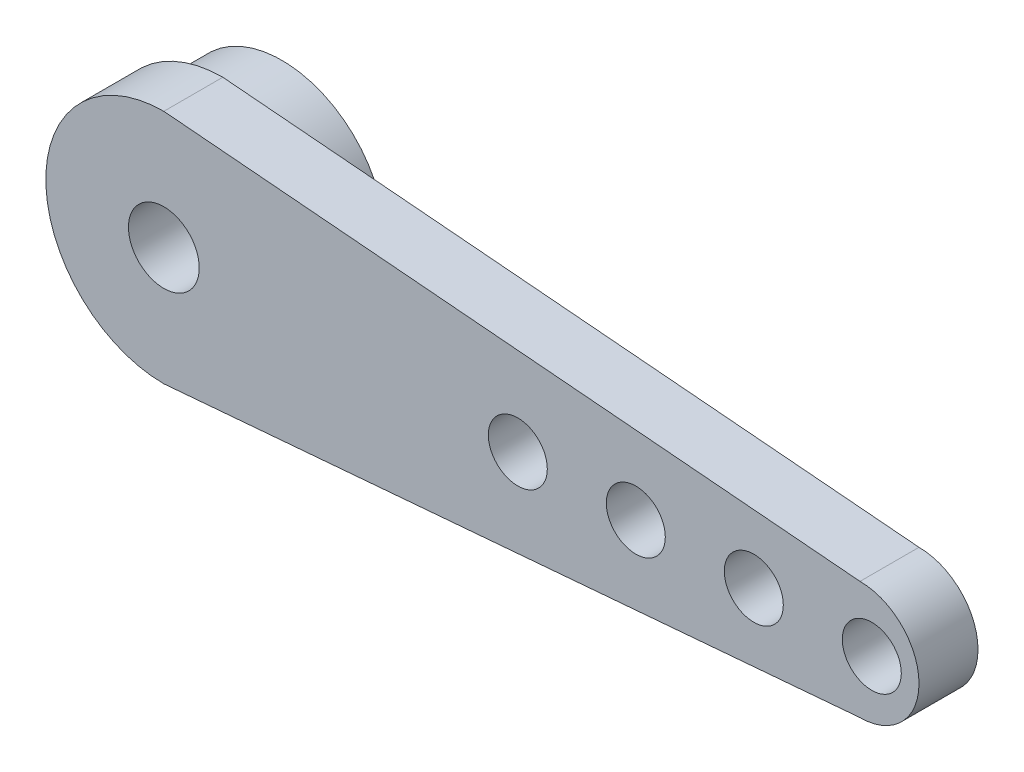
SolidWorks part; units mm, degrees
material "6061 Alloy"
ref_plane "Front Plane" through (0, 0, 0) normal (0, 0, 1) x (1, 0, 0)
ref_plane "Top Plane" through (0, 0, 0) normal (0, 1, 0) x (1, 0, 0)
ref_plane "Right Plane" through (0, 0, 0) normal (1, 0, 0) x (0, 0, -1)
sketch "Sketch1" plane through (0, 0, 0) normal (0, 0, 1) x (1, 0, 0)
  line L0 (0, 0) -> (27.5918, 0) construction
  line L1 (0, 5) -> (29.5, 2.5)
  line L2 (0, -5) -> (29.5, -2.5)
  line L3 (32, 0) -> (50.4925, 0) construction
  arc A0 (0.8414, 4.9287) -> (0.8414, -4.9287) centre (0, 0) ccw
  arc A1 (29.5, -2.5) -> (29.5, 2.5) centre (29.5, 0) ccw
  circle A2 centre (0, 0) radius 1.5
  circle A4 centre (15, 0) radius 1.25
  circle A5 centre (20, 0) radius 1.25
  circle A6 centre (25, 0) radius 1.25
  circle A7 centre (30, 0) radius 1.25
  point P5 (-5, 0)
  point P7 (32, 0)
  dimension "D1" = 37
  dimension "D2" = 2.5
  dimension "D3" = 3
  dimension "D6" = 5
  dimension "D7" = 2.5
  dimension "D9" = 30
  dimension "D4" = 15
  dimension "D5" = 20
  dimension "D8" = 25
extrude "Boss-Extrude1" add sketch "Sketch1" along normal blind 2.5 contours L2 A1 L1 A0 A7 A6 A5 A4 A2
sketch "Sketch2" plane through (0, 0, 0) normal (0, 0, -1) x (-1, 0, 0)
  circle A0 centre (0, 0) radius 2.85
  circle A1 centre (0, 0) radius 4.375
  dimension "D1" = 8.75
  dimension "D2" = 5.7
extrude "Boss-Extrude2" add sketch "Sketch2" along normal blind 2.5
